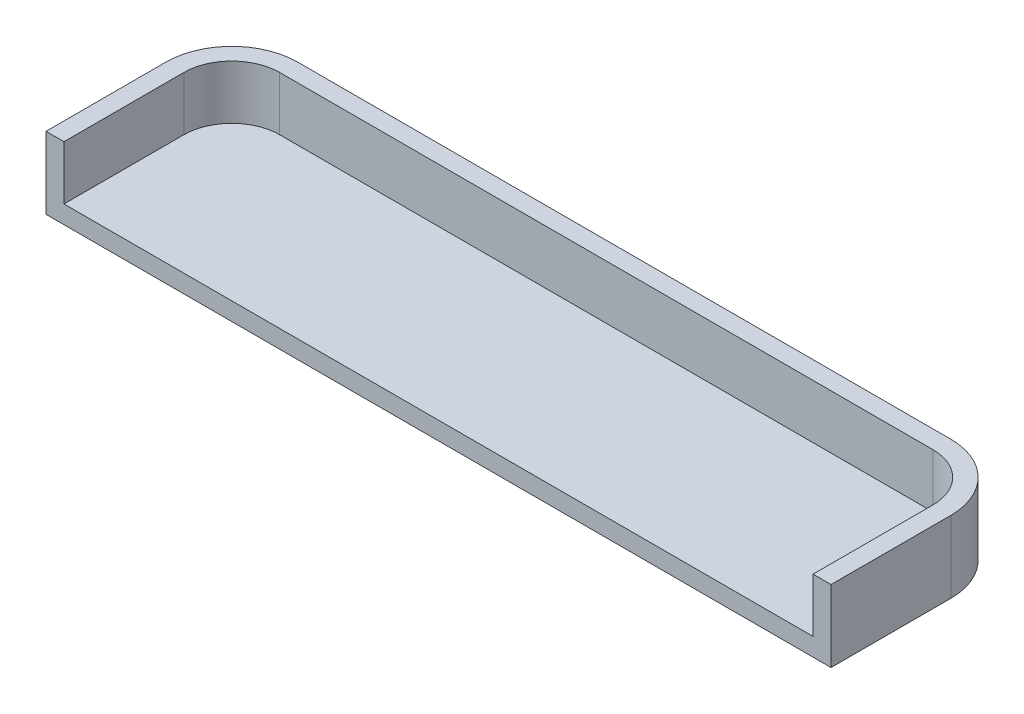
SolidWorks part; units mm, degrees
ref_plane "前视基准面" through (0, 0, 0) normal (0, 0, 1) x (1, 0, 0)
ref_plane "上视基准面" through (0, 0, 0) normal (0, 1, 0) x (1, 0, 0)
ref_plane "右视基准面" through (0, 0, 0) normal (1, 0, 0) x (0, 0, -1)
sketch "草图1" plane through (0, 0, 0) normal (0, 1, 0) x (1, 0, 0)
  line L0 (0, 0) -> (109, 0)
  line L1 (120, -11) -> (120, -31)
  line L2 (-11, -11) -> (-11, -31)
  line L3 (-11, -31) -> (120, -31)
  arc A0 (109, 0) -> (120, -11) centre (109, -11) cw
  arc A1 (0, 0) -> (-11, -11) centre (0, -11) ccw
  dimension "D1" = 11
  dimension "D2" = 11
  dimension "D3" = 109
  dimension "D4" = 20
extrude "凸台-拉伸1" add sketch "草图1" along normal blind 12
sketch "草图2" plane through (0, 12, 0) normal (0, 1, 0) x (1, 0, 0)
  line L0 (-8, -31) -> (-8, -11)
  line L1 (-11, -31) -> (120, -31) construction
  line L2 (0, -3) -> (109, -3)
  line L3 (117, -11) -> (117, -31)
  line L4 (117, -31) -> (-8, -31)
  line L5 (-11, -11) -> (-11, -31) construction
  line L6 (109, 0) -> (0, 0) construction
  arc A0 (-8, -11) -> (0, -3) centre (0, -11) cw
  arc A1 (109, -3) -> (117, -11) centre (109, -11) cw
  dimension "D1" = 8
  dimension "D3" = 8
  dimension "D2" = 109
  dimension "D4" = 3
  dimension "D5" = 3
extrude "切除-拉伸1" cut sketch "草图2" against normal blind 9
